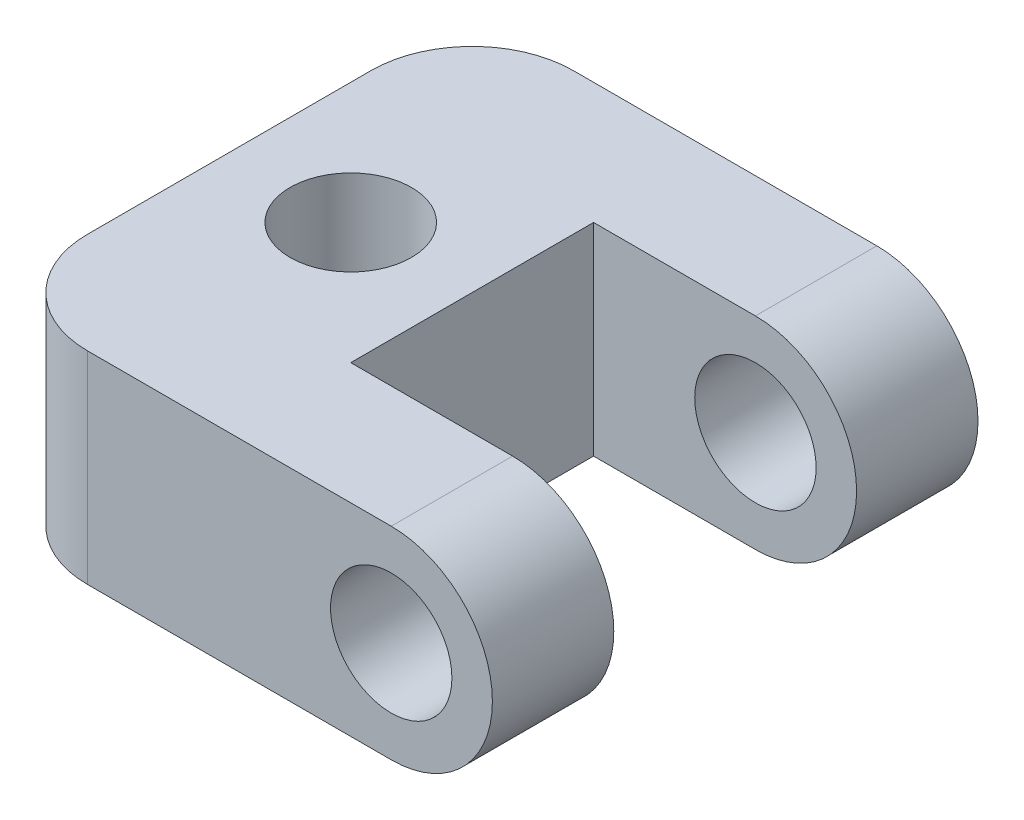
SolidWorks part; units mm, degrees
ref_plane "Front Plane" through (0, 0, 0) normal (0, 0, 1) x (1, 0, 0)
ref_plane "Top Plane" through (0, 0, 0) normal (0, 1, 0) x (1, 0, 0)
ref_plane "Right Plane" through (0, 0, 0) normal (1, 0, 0) x (0, 0, -1)
sketch "Sketch1" plane through (0, 0, 0) normal (0, 0, 1) x (1, 0, 0)
  line L0 (0, 0) -> (10, 0)
  line L1 (10, 5) -> (0, 5)
  line L2 (0, 5) -> (0, 0)
  arc A0 (10, 0) -> (10, 5) centre (10, 2.5) ccw
  dimension "D2" = 2.5
  dimension "D1" = 10
extrude "Boss-Extrude1" add sketch "Sketch1" against normal blind 12
sketch "Sketch2" plane through (0, 5, 0) normal (0, 1, 0) x (1, 0, 0)
  line L0 (12.5, 0) -> (12.5, 12) construction
  line L1 (6, 9) -> (12.5, 9)
  line L2 (6, 9) -> (6, 3)
  line L3 (6, 3) -> (12.5, 3)
  line L4 (12.5, 9) -> (12.5, 3)
  line L5 (10, 12) -> (0, 12) construction
  line L7 (10, 12) -> (10, 0) construction
  dimension "D1" = 6
  dimension "D2" = 3
  dimension "D3" = 4
extrude "Cut-Extrude1" cut sketch "Sketch2" against normal through all
sketch "Sketch3" plane through (0, 0, 0) normal (0, 0, 1) x (1, 0, 0)
  circle A0 centre (10, 2.5) radius 1.5
  dimension "D1" = 3
extrude "Cut-Extrude2" cut sketch "Sketch3" against normal blind 12
sketch "Sketch6" plane through (0, 5, 0) normal (0, 1, 0) x (1, 0, 0)
  line L0 (6, 6) -> (0, 6) construction
  line L1 (6, 9) -> (6, 3) construction
  line L2 (0, 12) -> (0, 0) construction
  circle A0 centre (3, 6) radius 1.5
  dimension "D1" = 3
extrude "Cut-Extrude3" cut sketch "Sketch6" against normal through all
fillet "Fillet1" radius 2.5 2 edges at (0, 2.5, -12) (0, 2.5, 0)
